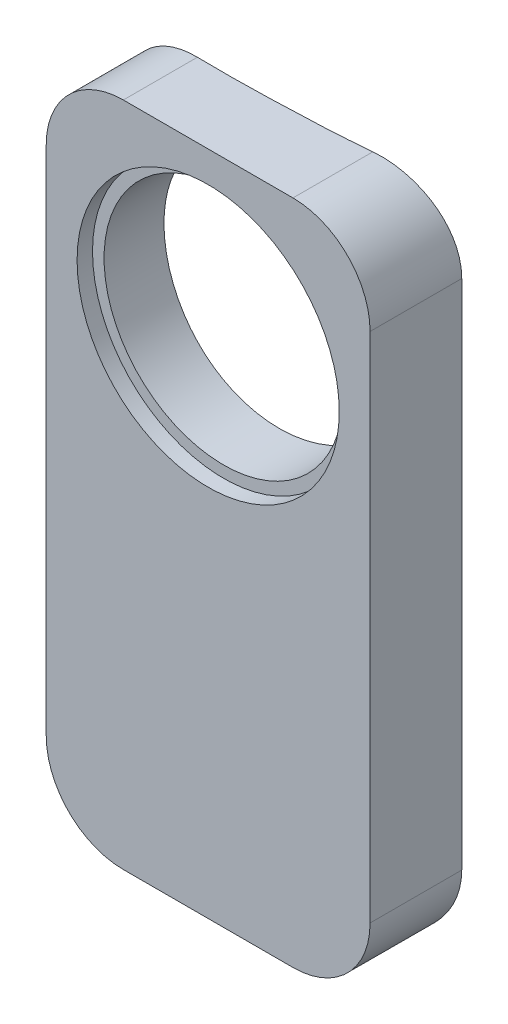
SolidWorks part; units mm, degrees
ref_plane "Front Plane" through (0, 0, 0) normal (0, 0, 1) x (1, 0, 0)
ref_plane "Top Plane" through (0, 0, 0) normal (0, 1, 0) x (1, 0, 0)
ref_plane "Right Plane" through (0, 0, 0) normal (1, 0, 0) x (0, 0, -1)
sketch "草图1" plane through (0, 0, 0) normal (0, 0, 1) x (1, 0, 0)
  line L0 (-10.5, 10.5) -> (10.5, -10.5) construction
  line L3 (-10.5, 10.5) -> (10.5, 10.5)
  line L4 (10.5, -10.5) -> (10.5, 10.5)
  line L5 (10.5, 10.5) -> (-10.5, -10.5) construction
  line L9 (10.5, -10.5) -> (10.5, -32.7185)
  line L10 (10.5, -32.7185) -> (-10.5, -32.7185)
  line L11 (-10.5, -32.7185) -> (-10.5, -10.5)
  line L12 (-10.5, 10.5) -> (-10.5, -10.5)
  dimension "D1" = 21
extrude "凸台-拉伸1" add sketch "草图1" along normal blind 6
sketch "草图4" plane through (0, 0, 6) normal (0, 0, 1) x (1, 0, 0)
  circle A0 centre (0, 0) radius 7.75
  point P2 (0, 0)
  point P3 (0, 0)
  point P4 (0.4915, 1.9661)
  dimension "D1" = 15.5
sketch "草图5" plane through (0, 0, 6) normal (0, 0, 1) x (1, 0, 0)
  circle A0 centre (0, 0) radius 8.5
  point P3 (0, 0)
  point P4 (0, 0)
  dimension "D1" = 17
sketch "草图8" plane through (0, 10.5, 0) normal (0, 1, 0) x (1, 0, 0)
  line L0 (-19.0205, 0.4766) -> (13.6565, 0.8442)
  spline S0 degree 3 poles (-19.0205, 0.4766) (-14.9079, -0.4443) (-8.4557, -1.3339) (2.5369, -1.1181) (9.3405, -0.6736) (13.6565, 0.8442) knots 0 0 0 0 0.383695 0.588358 1 1 1 1
extrude "切除-拉伸5" cut sketch "草图8" against normal through all
extrude "切除-拉伸6" cut sketch "草图4" against normal through all
fillet "圆角1" radius 5 4 edges at (-10.5, -32.7185, 3.4516) (10.5, -32.7185, 3.0278) (10.5, 10.5, 3.0278) (-10.5, 10.5, 3.4516)
extrude "切除-拉伸7" cut sketch "草图5" against normal blind 1
